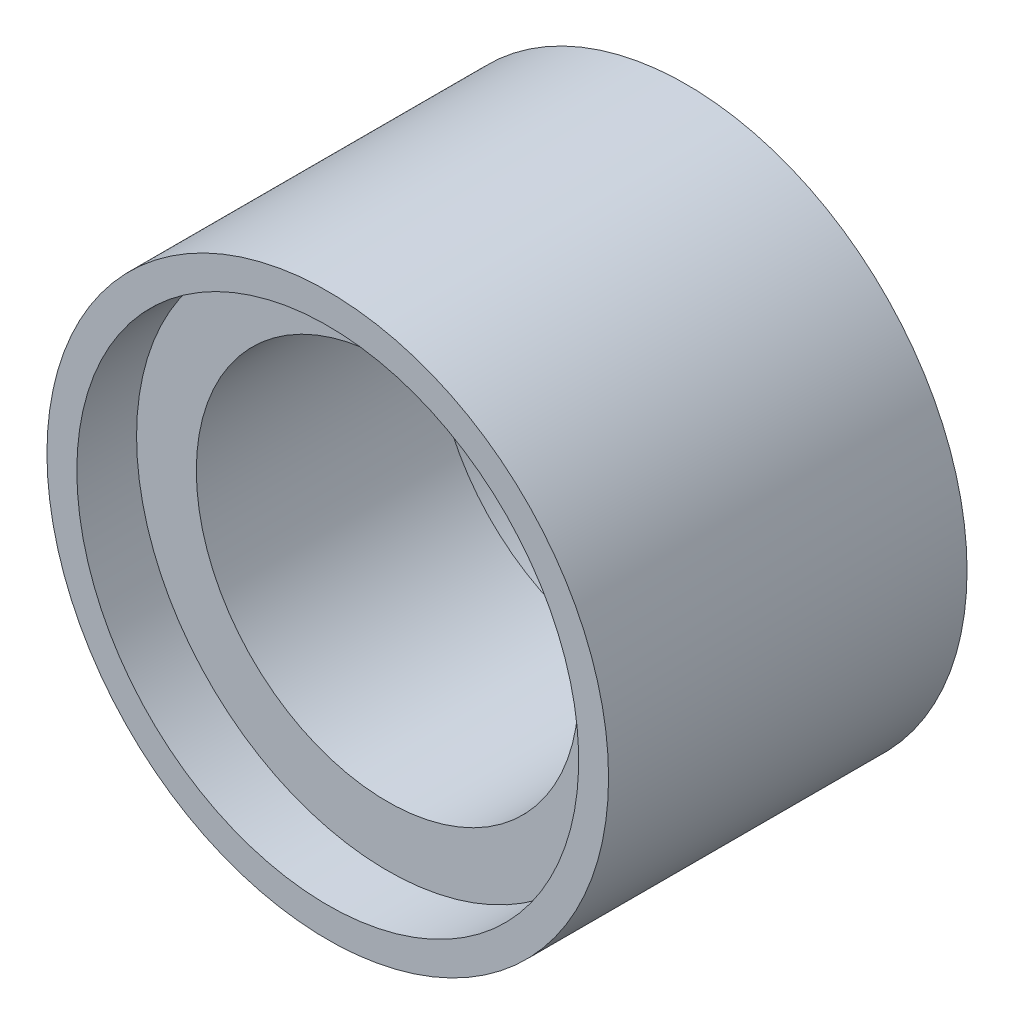
SolidWorks part; units mm, degrees
material "6063-O"
ref_plane "Front Plane" through (0, 0, 0) normal (0, 0, 1) x (1, 0, 0)
ref_plane "Top Plane" through (0, 0, 0) normal (0, 1, 0) x (1, 0, 0)
ref_plane "Right Plane" through (0, 0, 0) normal (1, 0, 0) x (0, 0, -1)
sketch "Sketch1" plane through (0, 0, 0) normal (0, 0, 1) x (1, 0, 0)
  circle A0 centre (0, 0) radius 23.5
  circle A1 centre (0, 0) radius 16
  dimension "D1" = 47
  dimension "D2" = 32
extrude "Boss-Extrude1" add sketch "Sketch1" along normal mid plane 20
sketch "Sketch2" plane through (0, 0, -10) normal (0, 0, -1) x (-1, 0, 0)
  circle A0 centre (0, 0) radius 21
  circle A1 centre (0, 0) radius 23.5
  dimension "D1" = 47
  dimension "D2" = 42
extrude "Boss-Extrude2" add sketch "Sketch2" along normal blind 5
mirror "Mirror1" about plane through (0, 0, 0) normal (0, 0, 1) of "Boss-Extrude2"
sketch "Sketch3" plane through (0, 0, -10) normal (0, 0, -1) x (-1, 0, 0)
  circle A0 centre (0, 0) radius 21
  circle A1 centre (0, 0) radius 15.05
extrude "Cut-Extrude1" [suppressed] cut sketch "Sketch3" against normal blind 1.8
mirror "Mirror2" [suppressed] about plane through (0, 0, 0) normal (0, 0, 1)
